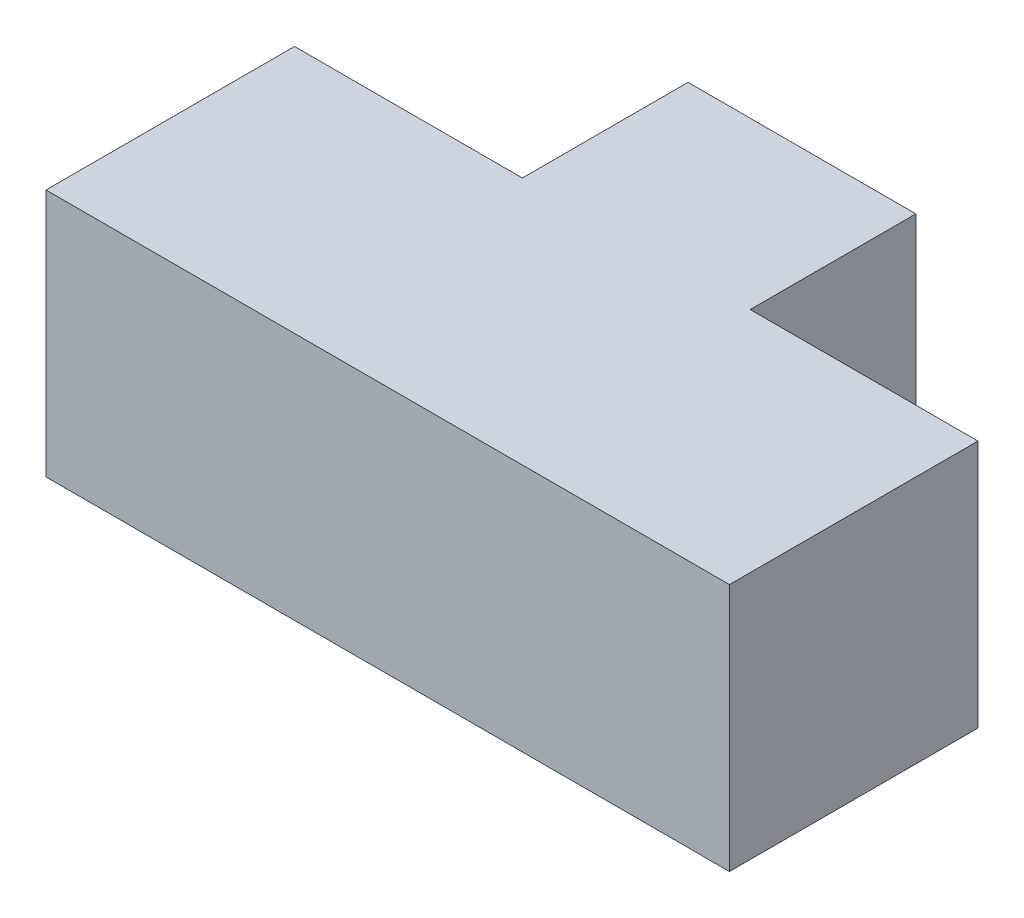
SolidWorks part; units mm, degrees
material "Copper"
ref_plane "Front Plane" through (0, 0, 0) normal (0, 0, 1) x (1, 0, 0)
ref_plane "Top Plane" through (0, 0, 0) normal (0, 1, 0) x (1, 0, 0)
ref_plane "Right Plane" through (0, 0, 0) normal (1, 0, 0) x (0, 0, -1)
sketch "Sketch1" plane through (0, 0, 0) normal (0, 1, 0) x (1, 0, 0)
  line L0 (0, 0) -> (209.55, 0)
  line L5 (0, 0) -> (0, 76.2)
  line L6 (0, 76.2) -> (69.85, 76.2)
  line L7 (69.85, 76.2) -> (69.85, 127)
  line L8 (69.85, 127) -> (139.7, 127)
  line L9 (139.7, 127) -> (139.7, 76.2)
  line L10 (139.7, 76.2) -> (209.55, 76.2)
  line L11 (209.55, 76.2) -> (209.55, 0)
  dimension "D1" = 50.8
  dimension "D2" = 69.85
  dimension "D3" = 76.2
  dimension "D4" = 209.55
extrude "Boss-Extrude1" add sketch "Sketch1" along normal blind 76.2
